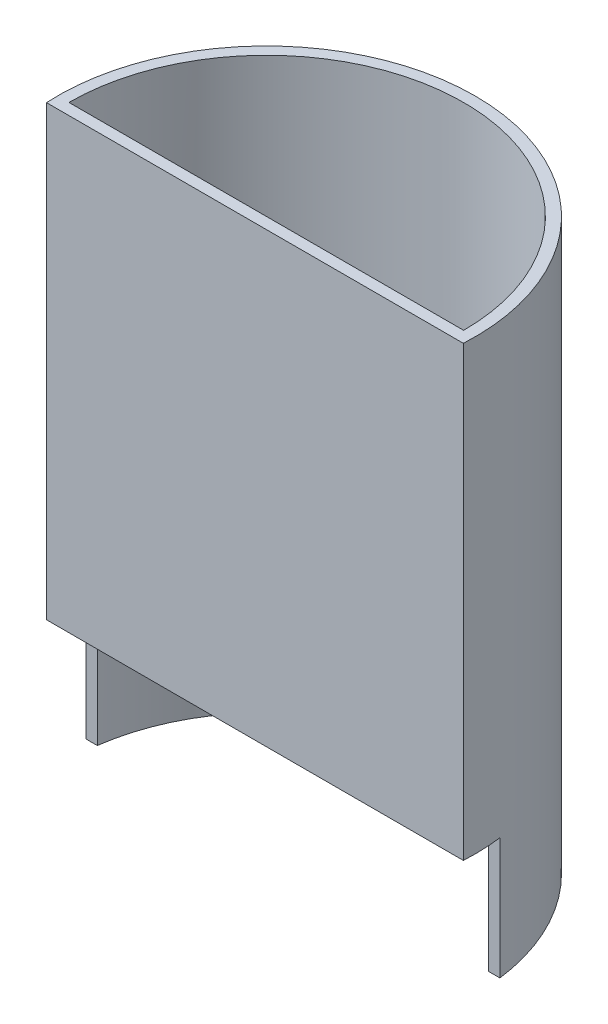
SolidWorks part; units mm, degrees
ref_plane "Front Plane" through (0, 0, 0) normal (0, 0, 1) x (1, 0, 0)
ref_plane "Top Plane" through (0, 0, 0) normal (0, 1, 0) x (1, 0, 0)
ref_plane "Right Plane" through (0, 0, 0) normal (1, 0, 0) x (0, 0, -1)
sketch "Sketch1" plane through (0, 0, 0) normal (0, 1, 0) x (1, 0, 0)
  line L0 (-52, 0) -> (52, 0)
  line L1 (-54.9181, -3) -> (54.9181, -3)
  arc A0 (52, 0) -> (-52, 0) centre (0, 0) ccw
  arc A1 (54.9181, -3) -> (-54.9181, -3) centre (0, 0) ccw
  dimension "D1" = 3
extrude "Boss-Extrude1" add sketch "Sketch1" along normal blind 150
sketch "Sketch3" plane through (0, 0, 3) normal (0, 0, 1) x (1, 0, 0)
  line L2 (54.9181, 18) -> (-54.9181, 18)
  line L3 (54.9181, 150) -> (54.9181, 0) construction
  line L4 (-54.9181, 150) -> (-54.9181, 0) construction
  line L5 (-54.9181, 18) -> (-54.9181, 32)
  line L6 (-54.9181, 32) -> (54.9181, 32)
  line L7 (54.9181, 32) -> (54.9181, 18)
  dimension "D1" = 14
extrude "Cut-Extrude3" cut sketch "Sketch3" against normal blind 5 contours L6 L7 L2 L5
sketch "Sketch4" plane through (0, 0, 3) normal (0, 0, 1) x (1, 0, 0)
  line L0 (0, 0) -> (62.1102, 0)
  line L1 (0, 32) -> (64.1202, 32) construction
  line L2 (-54.9181, 32) -> (54.9181, 32) construction
  line L3 (64.1202, 32) -> (-64.7232, 32) construction
  line L4 (62.1102, 0) -> (62.1102, 32)
  line L5 (62.1102, 32) -> (-64.7232, 32)
  line L6 (-64.7232, 32) -> (-64.7232, 0)
  line L7 (-64.7232, 0) -> (0, 0)
extrude "Cut-Extrude4" cut sketch "Sketch4" against normal blind 10
ref_plane "Plane1" through (0, 32, 0) normal (0, -1, 0) x (-1, 0, 0)
sketch "Sketch6" plane through (0, 32, 0) normal (0, -1, 0) x (-1, 0, 0)
  line L0 (-52, 0) -> (52, 0) construction
  line L1 (27.7128, 44) -> (0, 0)
  line L2 (0, 0) -> (52, 0)
  arc A0 (52, 0) -> (27.7128, 44) centre (0, 0) ccw
  arc A1 (52, 0) -> (51.5267, 7) centre (0, 0) ccw construction
  dimension "D1" = 44
extrude "Boss-Extrude2" add sketch "Sketch6" against normal blind 15
fillet "Fillet1" [suppressed] radius 15
draft "Draft2" type of draft neutral plane draft angle 60 faces to draft 1 face at (-28.4605, 47, -15.7097) neutral plane through (-27.7128, 47, -44) neutral plane normal (0.8462, 0, -0.5329) parameters "D1"=60
